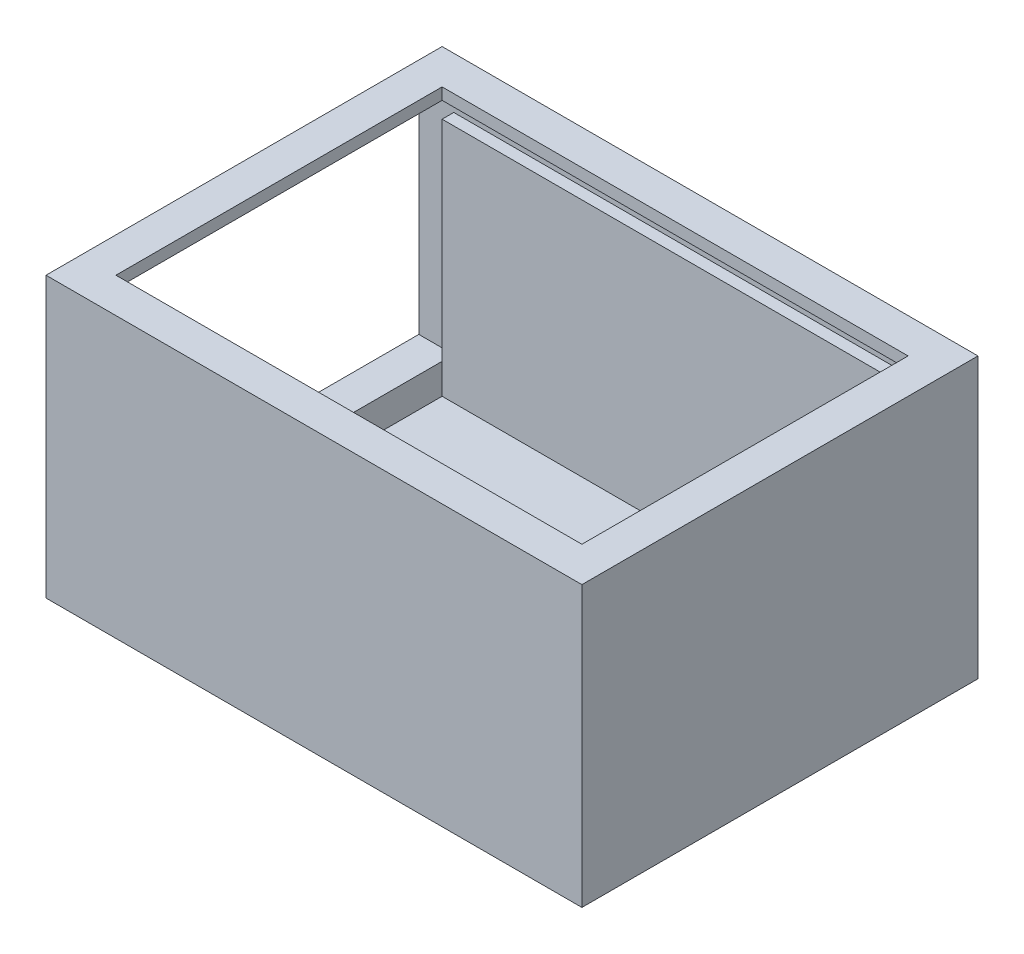
SolidWorks part; units mm, degrees
ref_plane "Front Plane" through (0, 0, 0) normal (0, 0, 1) x (1, 0, 0)
ref_plane "Top Plane" through (0, 0, 0) normal (0, 1, 0) x (1, 0, 0)
ref_plane "Right Plane" through (0, 0, 0) normal (1, 0, 0) x (0, 0, -1)
sketch "Sketch1" plane through (0, 0, 0) normal (0, 1, 0) x (1, 0, 0)
  line L1 (0, 0) -> (115, 0)
  line L2 (0, 0) -> (0, 85)
  line L3 (0, 85) -> (115, 85)
  line L4 (115, 0) -> (115, 85)
  dimension "D1" = 85
  dimension "D2" = 115
extrude "Boss-Extrude1" add sketch "Sketch1" along normal blind 60
sketch "Sketch2" plane through (0, 60, 0) normal (0, 1, 0) x (1, 0, 0)
  line L0 (7.5, 34.9909) -> (0, 34.9909) construction
  line L6 (7.5, 77.5) -> (107.5, 77.5)
  line L8 (7.5, 77.5) -> (7.5, 7.5)
  line L10 (7.5, 7.5) -> (107.5, 7.5)
  line L12 (107.5, 77.5) -> (107.5, 7.5)
  line L13 (0, 85) -> (0, 0) construction
  line L14 (42.7951, 77.5) -> (42.7951, 85) construction
  line L15 (115, 85) -> (0, 85) construction
  line L16 (107.5, 48.9379) -> (115, 48.9379) construction
  line L17 (115, 0) -> (115, 85) construction
  line L18 (51.6954, 0) -> (51.6954, 7.5) construction
  line L19 (0, 0) -> (115, 0) construction
  dimension "D1" = 70
  dimension "D2" = 100
extrude "Cut-Extrude1" cut sketch "Sketch2" against normal blind 57.5
sketch "Sketch3" plane through (0, 0, 0) normal (-1, 0, 0) x (0, 0, 1)
  line L0 (-80, 55.75) -> (-85, 55.75) construction
  line L1 (-80, 57.5) -> (-5, 57.5)
  line L2 (-80, 57.5) -> (-80, 54)
  line L3 (-80, 54) -> (-5, 54)
  line L4 (-5, 57.5) -> (-5, 54)
  line L5 (-85, 60) -> (-85, 0) construction
  line L6 (-42.5, 57.5) -> (-42.5, 60) construction
  line L7 (-85, 60) -> (0, 60) construction
  line L8 (-5, 55.75) -> (0, 55.75) construction
  line L9 (0, 60) -> (0, 0) construction
  dimension "D1" = 75
  dimension "D2" = 3.5
extrude "Cut-Extrude2" cut sketch "Sketch3" against normal blind 109
sketch "Sketch4" plane through (0, 0, 0) normal (-1, 0, 0) x (0, 0, 1)
  line L1 (-80, 54) -> (-5.0036, 54)
  line L2 (-80, 54) -> (-80, 9)
  line L3 (-80, 9) -> (-5.0036, 9)
  line L4 (-5.0036, 54) -> (-5.0036, 9)
  dimension "D1" = 45
  dimension "D2" = 74.9964
extrude "Cut-Extrude3" cut sketch "Sketch4" against normal blind 7.5
